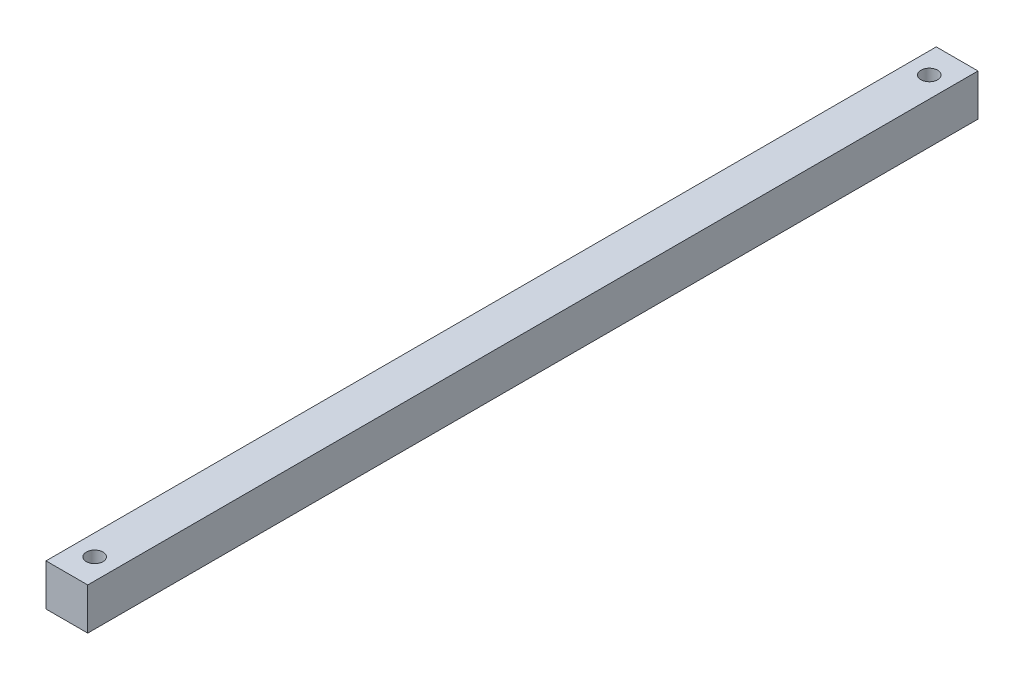
SolidWorks part; units mm, degrees
ref_plane "前视基准面" through (0, 0, 0) normal (0, 0, 1) x (1, 0, 0)
ref_plane "上视基准面" through (0, 0, 0) normal (0, 1, 0) x (1, 0, 0)
ref_plane "右视基准面" through (0, 0, 0) normal (1, 0, 0) x (0, 0, -1)
other "Configuration Table"
sketch "草图1" plane through (0, 0, 0) normal (0, 0, 1) x (1, 0, 0)
  line L1 (0, 0) -> (15, 0)
  line L2 (0, 0) -> (0, -15)
  line L3 (0, -15) -> (15, -15)
  line L4 (15, 0) -> (15, -15)
  dimension "D1" = 15
  dimension "D2" = 15
extrude "凸台-拉伸1" add sketch "草图1" along normal blind 320
sketch "草图2" plane through (0, 0, 0) normal (0, 1, 0) x (1, 0, 0)
  line L0 (7.5, 0) -> (7.5, -320) construction
  line L1 (15, 0) -> (0, 0) construction
  line L2 (15, -320) -> (0, -320) construction
  circle A0 centre (7.5, -310) radius 3
  circle A1 centre (7.5, -10) radius 3
  dimension "D1" = 6
  dimension "D2" = 6
  dimension "D3" = 300
  dimension "D4" = 10
extrude "切除-拉伸1" cut sketch "草图2" against normal through all
